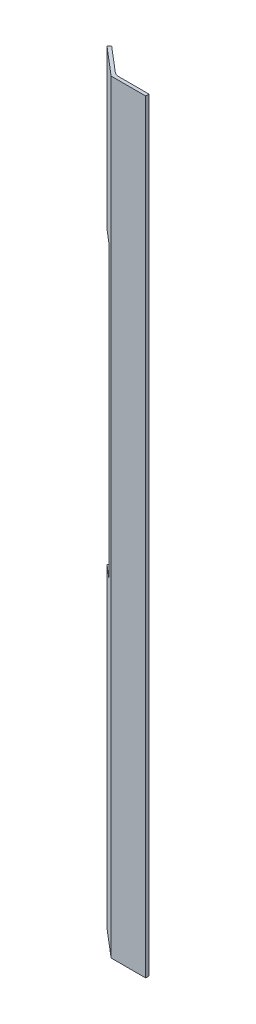
SolidWorks part; units mm, degrees
ref_plane "Спереди" through (0, 0, 0) normal (0, 0, 1) x (1, 0, 0)
ref_plane "Сверху" through (0, 0, 0) normal (0, 1, 0) x (1, 0, 0)
ref_plane "Справа" through (0, 0, 0) normal (1, 0, 0) x (0, 0, -1)
sketch "Эскиз1" plane through (0, 0, 0) normal (0, 1, 0) x (1, 0, 0)
  line L0 (-20.5084, 12.7927) -> (-19.212, 14.3155)
  line L1 (-1.1334, 0.4869) -> (17.1228, 0.4869)
  line L2 (-19.212, 14.3155) -> (-4.3752, 1.6802)
  line L3 (-20.5084, 12.7927) -> (-3.7046, -1.5131)
  line L4 (-3.7046, -1.5131) -> (17.1228, -1.5131)
  line L5 (17.1228, -1.5131) -> (17.1228, 0.4869)
  arc A0 (-1.1334, 0.4869) -> (-4.3752, 1.6802) centre (-1.1334, 5.4869) cw
  dimension "D1" = 5
extrude "Вытянуть1" add sketch "Эскиз1" along normal blind 460 from offset 40
sketch "Эскиз2" plane through (-2.3036, 0, 2.7059) normal (-0.6482, 0, 0.7614) x (0.7614, 0, 0.6482)
  line L0 (-29.2499, 538.7137) -> (-29.2499, 0) construction
  line L1 (-29.2499, 404.5977) -> (-14.4324, 404.5977)
  line L2 (-29.2499, 404.5977) -> (-29.2499, 229.6358)
  line L3 (-29.2499, 229.6358) -> (-14.4324, 229.6358)
  line L4 (-14.4324, 404.5977) -> (-14.4324, 229.6358)
extrude "Вырез-Вытянуть1" cut sketch "Эскиз2" against normal through all
